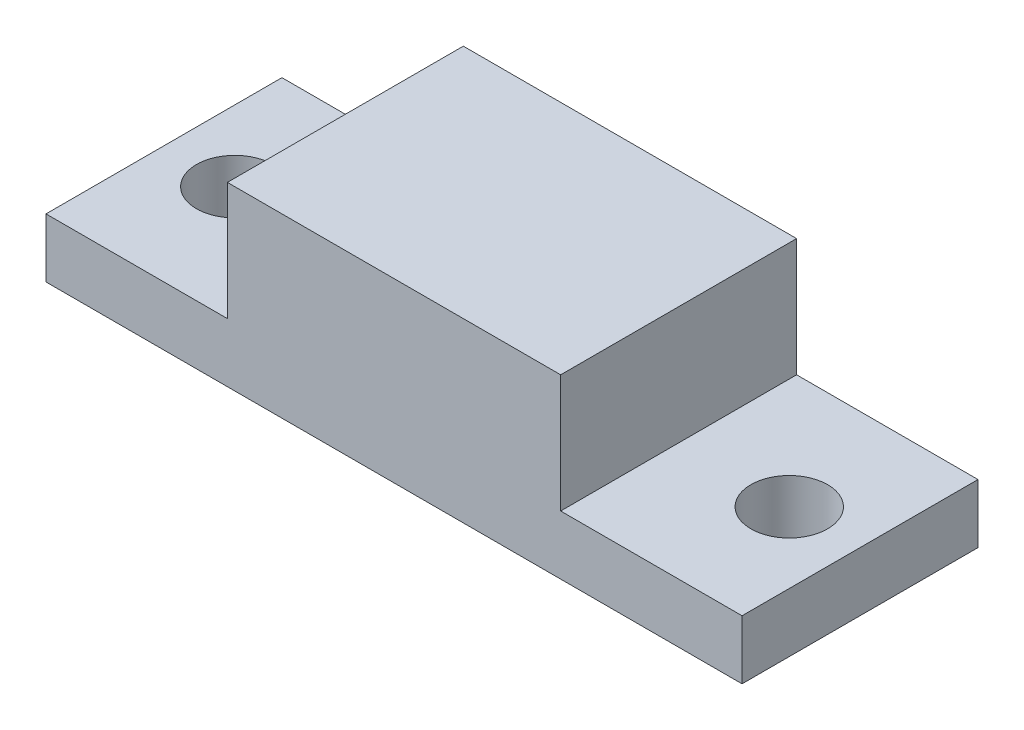
SolidWorks part; units mm, degrees
material "ABS"
ref_plane "Спереди" through (0, 0, 0) normal (0, 0, 1) x (1, 0, 0)
ref_plane "Сверху" through (0, 0, 0) normal (0, 1, 0) x (1, 0, 0)
ref_plane "Справа" through (0, 0, 0) normal (1, 0, 0) x (0, 0, -1)
sketch "Эскиз1" plane through (0, 0, 0) normal (0, 0, 1) x (1, 0, 0)
  line L0 (-5.65, 0) -> (5.65, 0)
  line L1 (5.65, 0) -> (5.65, -4)
  line L2 (5.65, -4) -> (11.8, -4)
  line L3 (11.8, -4) -> (11.8, -6)
  line L4 (11.8, -6) -> (-11.8, -6)
  line L5 (-11.8, -6) -> (-11.8, -4)
  line L6 (-11.8, -4) -> (-5.65, -4)
  line L7 (-5.65, -4) -> (-5.65, 0)
  line L8 (0, 0) -> (0, 9.8962) construction
  dimension "D1" = 23.6
  dimension "D2" = 11.3
  dimension "D3" = 4
  dimension "D4" = 2
extrude "Бобышка-Вытянуть1" add sketch "Эскиз1" along normal blind 8
sketch "Эскиз2" plane through (0, -6, 0) normal (0, -1, 0) x (1, 0, 0)
  line L0 (0, 0) -> (0, 17.1981) construction
  line L2 (-11.8, 8) -> (11.8, 8) construction
  circle A0 centre (-9.4, 4) radius 1.3
  circle A1 centre (9.4, 4) radius 1.3
  dimension "D2" = 2.6
  dimension "D1" = 4
  dimension "D3" = 18.8
extrude "Вырез-Вытянуть1" cut sketch "Эскиз2" against normal up to next
